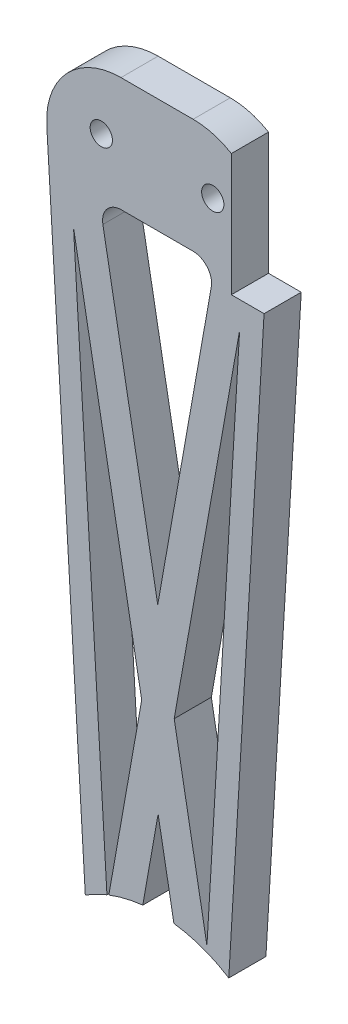
SolidWorks part; units mm, degrees
ref_plane "Front Plane" through (0, 0, 0) normal (0, 0, 1) x (1, 0, 0)
ref_plane "Top Plane" through (0, 0, 0) normal (0, 1, 0) x (1, 0, 0)
ref_plane "Right Plane" through (0, 0, 0) normal (1, 0, 0) x (0, 0, -1)
sketch "Sketch1" plane through (0, 0, 0) normal (0, 0, 1) x (1, 0, 0)
  line L0 (-30, 0) -> (30, 0)
  line L1 (0, 0) -> (15, 0)
  line L2 (55, 0) -> (-55, 0) construction
  line L3 (0, 0) -> (0, -210)
  line L4 (0, -44.7868) -> (0, 44.7868) construction
  line L5 (0, 0) -> (30, 0)
  line L6 (0, 0) -> (-30, 0)
  line L7 (0, 0) -> (-15, 0)
  line L8 (-6, -215) -> (6, -215)
  line L9 (-6, -215) -> (-6, -205)
  line L10 (-6, -205) -> (6, -205)
  line L11 (6, -215) -> (6, -205)
  line L12 (-6, -215) -> (6, -205) construction
  line L13 (-6, -205) -> (6, -215) construction
  line L14 (0, 0) -> (0, 15)
  line L15 (-30, 0) -> (-17.5, -210)
  line L16 (-30, 0) -> (30, 0)
  line L17 (-30, 0) -> (-30, 15.7704)
  line L18 (-30, 15.7704) -> (30, 15.7704)
  line L19 (30, 0) -> (30, 15.7704)
  line L20 (30, 0) -> (17.5, -210)
  circle A0 centre (15, 0) radius 3
  circle A1 centre (-15, 0) radius 3
  circle A2 centre (0, -210) radius 17.5
  point P4 (0, 0)
  dimension "D7" = 6
  dimension "D9" = 6
  dimension "D11" = 35
  dimension "D1" = 210
  dimension "D2" = 30
  dimension "D3" = 30
  dimension "D4" = 10
  dimension "D5" = 12
  dimension "D6" = 15
  dimension "D8" = 15
  dimension "D10" = 15
extrude "Boss-Extrude2" add sketch "Sketch1" along normal blind 10
fillet "Fillet1" radius 20 1 edges at (-30, 15.7704, 5)
fillet "Fillet2" radius 20 1 edges at (30, 15.7704, 5)
sketch "Sketch4" plane through (0, 0, 10) normal (0, 0, 1) x (1, 0, 0)
  line L0 (-29.3398, -11.0918) -> (-23.3398, -11.0918)
  line L1 (-29.6775, -5.418) -> (-17.5, -210) construction
  line L2 (29.3911, -10.23) -> (23.3911, -10.23)
  line L3 (29.6775, -5.418) -> (17.5, -210) construction
  line L4 (-18.3824, -195.1758) -> (-12.3824, -195.1758)
  line L5 (18.3824, -195.1758) -> (12.3824, -195.1758)
  line L6 (-12.3824, -195.1758) -> (-23.5439, -7.6624)
  line L7 (23.3911, -7.6624) -> (11.6198, -205.4193)
  line L8 (-22.9543, -15) -> (22.9543, -15)
  line L9 (-8.4362, -200.1287) -> (-16.4545, -196.0413)
  line L10 (9.2183, -200.015) -> (17.2308, -195.9163)
  line L11 (9.2183, -200.015) -> (-24.5465, -14.245)
  line L12 (17.2308, -195.9163) -> (-16.534, -10.1463)
  line L13 (-24.5465, -14.245) -> (-16.534, -10.1463)
  line L14 (-8.4362, -200.1287) -> (24.4903, -14.4152)
  line L15 (-16.4545, -196.0413) -> (16.472, -10.3277)
  line L16 (24.4903, -14.4152) -> (16.472, -10.3277)
  circle A0 centre (0, -210) radius 17.5
  circle A1 centre (15, 0) radius 15
  point P25 (0, -15)
  dimension "D5" = 15
  dimension "D1" = 6
  dimension "D2" = 6
  dimension "D3" = 6
  dimension "D4" = 6
  dimension "D6" = 9
  dimension "D7" = 9
extrude "Cut-Extrude1" cut sketch "Sketch4" against normal blind 10 contours L12 L15 L8 | L6 L15 L11 | L14 L12 L7 | A0 L11 L14
fillet "Fillet3" radius 5 4 edges at (8.2256, -194.5537, 5) (-7.3724, -194.1287, 5) (-15.6518, -15, 5) (15.6436, -15, 5)
sketch "Sketch5" plane through (0, 0, 10) normal (0, 0, 1) x (1, 0, 0)
  line L0 (15, 0) -> (30, 0)
  line L1 (55, 0) -> (-55, 0) construction
  line L2 (30, 0) -> (30, -20)
  line L3 (0, -175.7959) -> (34.2041, -175.7959)
  line L5 (30, -20) -> (30, 0)
  line L8 (0, -175.7959) -> (-19.536, -175.7959)
  line L9 (-29.6775, -5.418) -> (-17.5, -210) construction
  line L12 (30, 0) -> (20, 0)
  line L17 (30, 0) -> (30, 24.03)
  line L18 (30, 24.03) -> (20, 24.03)
  line L19 (20, 0) -> (20, 24.03)
  line L20 (30, 0) -> (20, 0)
  line L21 (30, 0) -> (30, -20)
  line L22 (30, -20) -> (20, -20)
  line L23 (20, 0) -> (20, -20)
  circle A0 centre (0, -210) radius 30
  circle A1 centre (0, -210) radius 34.2041
  circle A2 centre (0, -210) radius 36
  line M1 (17.5, -210) -> (29.6775, -5.418)
  arc M2 (29.6775, -5.418) -> (9.7128, 15.7704) centre (9.7128, -4.2296) ccw
  line M5 (-29.6775, -5.418) -> (-17.5, -210)
  arc M6 (-17.5, -210) -> (17.5, -210) centre (0, -210) ccw
  line M9 (-6, -215) -> (-6, -205)
  line M10 (-6, -205) -> (6, -205)
  line M11 (6, -205) -> (6, -215)
  line M12 (6, -215) -> (-6, -215)
  line M18 (0.2916, -150.9016) -> (6.7953, -186.6842)
  arc M19 (6.7953, -186.6842) -> (1.459, -192.5609) centre (1.8759, -187.5783) cw
  arc M20 (1.459, -192.5609) -> (-0.8744, -192.5219) centre (0, -210) ccw
  arc M21 (-0.8744, -192.5219) -> (-6.0474, -186.6552) centre (-1.1242, -187.5281) cw
  line M22 (-6.0474, -186.6552) -> (0.2916, -150.9016)
  line M26 (-4.1342, -126.5515) -> (-13.3673, -178.6289)
  line M27 (-13.3673, -178.6289) -> (-22.473, -25.6531)
  dimension "D3" = 60
  dimension "D4" = 36
  dimension "D1" = 15
  dimension "D2" = 20
  dimension "D5" = 24.03
  dimension "D6" = 10
  dimension "D7" = 20
  dimension "D8" = 10
extrude "Cut-Extrude5" cut sketch "Sketch5" against normal blind 10 contours L0 L23 L22 M1 M2 | L19 L0 M2 | L3 A2 M18 | A2 L3 A1 M1 M18 | A1 A0 M1 M18 | A0 M1 M18 M19 M20 M21 M22 M5 M6 M12 M9 M10 M11 | L8 A2 A1 M26 M22 | A2 L8 M22 | A2 A1 M27 M5 | A1 A0 M22 M26 M27 M5
